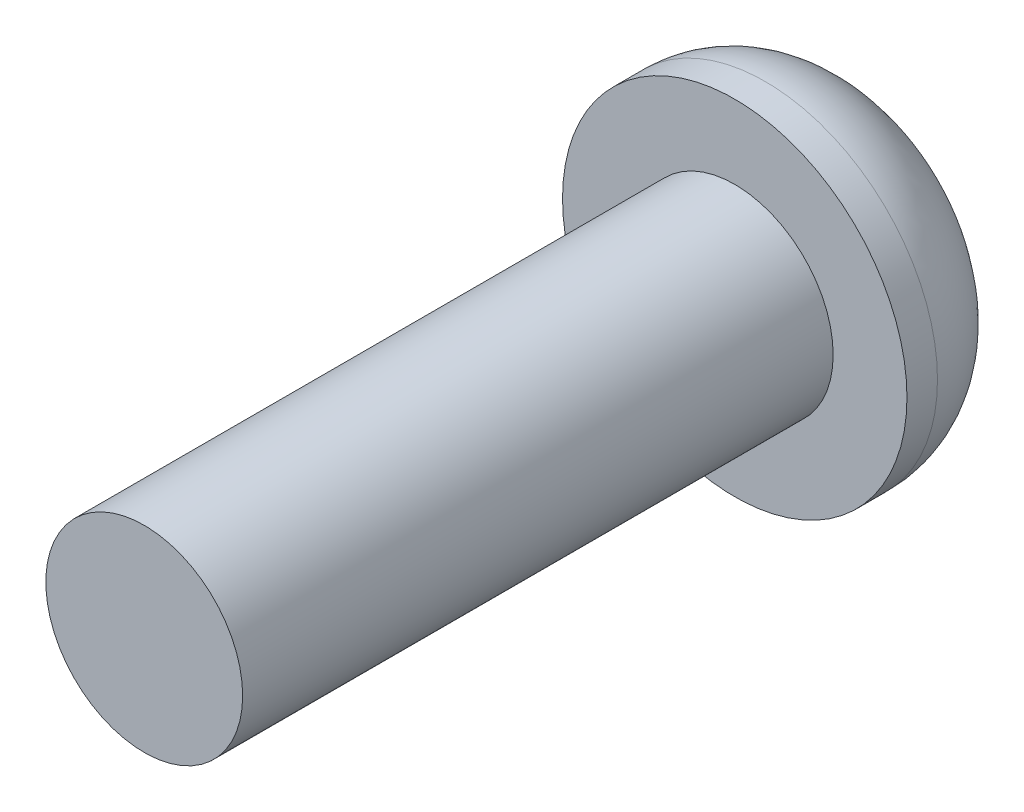
SolidWorks part; units mm, degrees
ref_plane "前视基准面" through (0, 0, 0) normal (0, 0, 1) x (1, 0, 0)
ref_plane "上视基准面" through (0, 0, 0) normal (0, 1, 0) x (1, 0, 0)
ref_plane "右视基准面" through (0, 0, 0) normal (1, 0, 0) x (0, 0, -1)
sketch "草图1" plane through (0, 0, 0) normal (0, 0, 1) x (1, 0, 0)
  circle A0 centre (0, 0) radius 1
extrude "凸台-拉伸1" add sketch "草图1" along normal blind 6
sketch "草图2" plane through (0, 0, 0) normal (0, 0, -1) x (-1, 0, 0)
  circle A0 centre (0, 0) radius 1.75
extrude "凸台-拉伸2" add sketch "草图2" along normal blind 1.31
fillet "圆角1" radius 1 1 edges at (-1.75, 0, -1.31)
